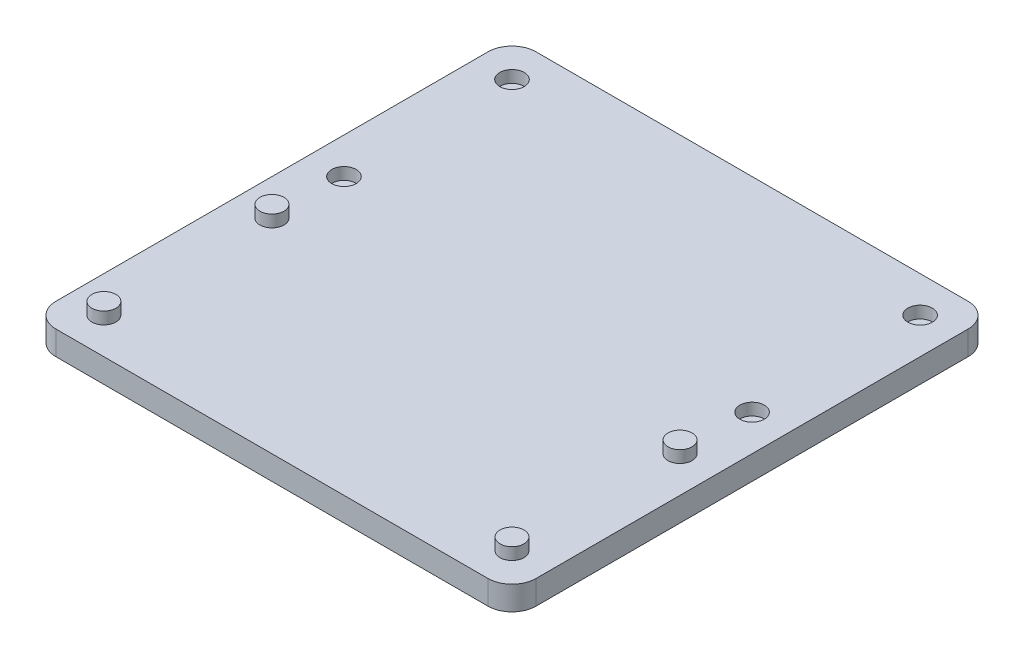
SolidWorks part; units mm, degrees
ref_plane "正面" through (0, 0, 0) normal (0, 0, 1) x (1, 0, 0)
ref_plane "平面" through (0, 0, 0) normal (0, 1, 0) x (1, 0, 0)
ref_plane "右側面" through (0, 0, 0) normal (1, 0, 0) x (0, 0, -1)
sketch "ｽｹｯﾁ1" plane through (0, 0, 0) normal (0, 1, 0) x (1, 0, 0)
  line L1 (-100, -100) -> (100, -100)
  line L2 (-100, -100) -> (-100, 100)
  line L3 (-100, 100) -> (100, 100)
  line L4 (100, -100) -> (100, 100)
  line L5 (-100, -100) -> (100, 100) construction
  line L6 (-100, 100) -> (100, -100) construction
  point P0 (0, 0)
  dimension "D1" = 200
  dimension "D2" = 200
extrude "ﾎﾞｽ - 押し出し1" add sketch "ｽｹｯﾁ1" along normal blind 10
sketch "ｽｹｯﾁ2" plane through (0, 10, 0) normal (0, 1, 0) x (1, 0, 0)
  line L19 (-100, 100) -> (-100, -100) construction
  line L20 (100, -100) -> (100, 100) construction
  line L21 (-100, -100) -> (100, -100) construction
  circle A0 centre (-85, -15) radius 5
  circle A1 centre (-85, -85) radius 5
  circle A2 centre (85, -85) radius 5
  circle A3 centre (85, -15) radius 5
  dimension "D1" = 10
  dimension "D2" = 15
  dimension "D3" = 15
  dimension "D4" = 15
  dimension "D5" = 15
extrude "ﾎﾞｽ - 押し出し2" add sketch "ｽｹｯﾁ2" along normal blind 5
fillet "ﾌｨﾚｯﾄ1" radius 10 4 edges at (100, 5, -100) (100, 5, 100) (-100, 5, 100) (-100, 5, -100)
sketch "ｽｹｯﾁ3" plane through (0, 10, 0) normal (0, 1, 0) x (1, 0, 0)
  line L0 (90, 100) -> (-90, 100) construction
  line L1 (-100, 90) -> (-100, -90) construction
  line L2 (100, -90) -> (100, 90) construction
  circle A0 centre (-85, 85) radius 5.1
  circle A1 centre (85, 85) radius 5.1
  circle A2 centre (-85, 15) radius 5.1
  circle A3 centre (85, 15) radius 5.1
  point P8 (0, 0)
  point P9 (-84.8052, 31.9924)
  point P10 (0, 0)
  point P11 (0, 0)
  point P12 (-84.8052, 87.5982)
  point P13 (0, 0)
  point P14 (0, 0)
  dimension "D1" = 10.2
  dimension "D2" = 15
  dimension "D3" = 15
  dimension "D4" = 15
  dimension "D5" = 15
extrude "ｶｯﾄ - 押し出し1" cut sketch "ｽｹｯﾁ3" against normal blind 5
